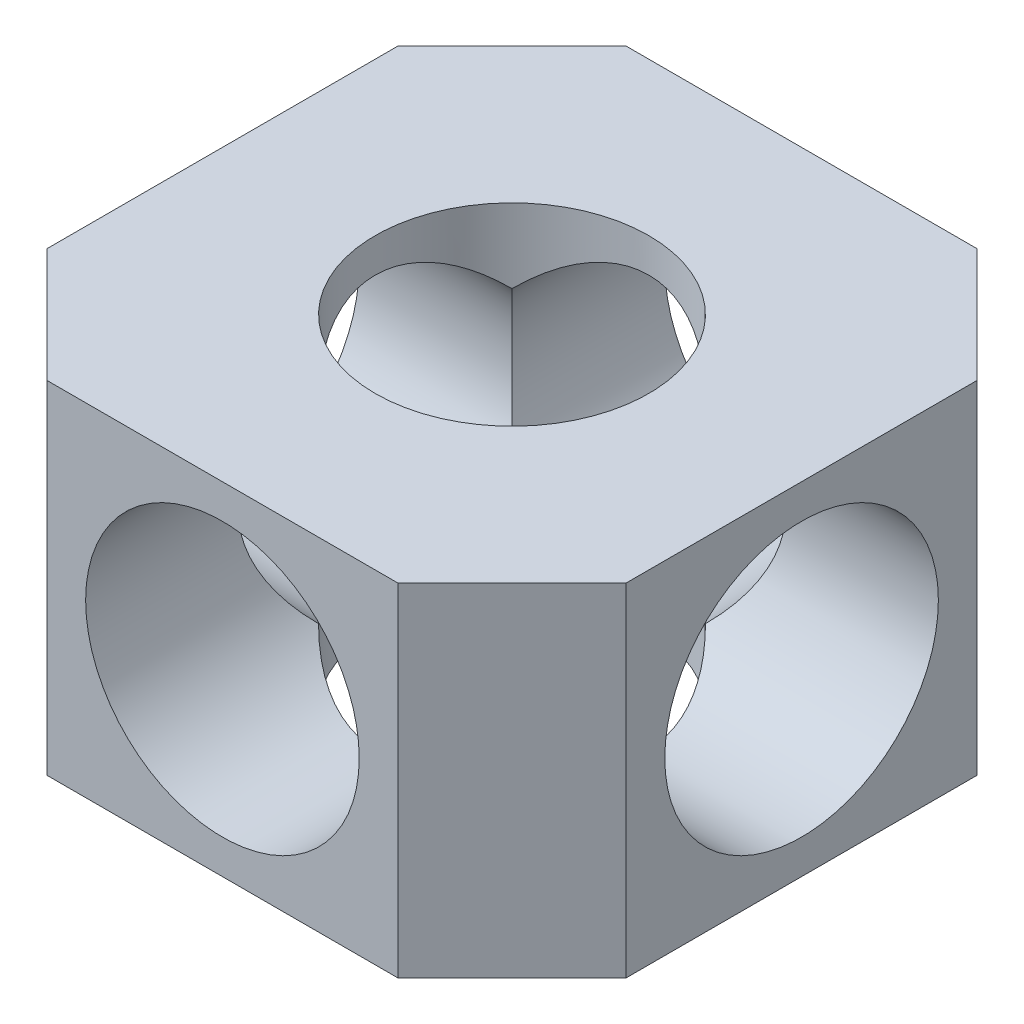
SolidWorks part; units mm, degrees
ref_plane "Front Plane" through (0, 0, 0) normal (0, 0, 1) x (1, 0, 0)
ref_plane "Top Plane" through (0, 0, 0) normal (0, 1, 0) x (1, 0, 0)
ref_plane "Right Plane" through (0, 0, 0) normal (1, 0, 0) x (0, 0, -1)
sketch "Sketch2" plane through (0, 0, 0) normal (0, 1, 0) x (1, 0, 0)
  line L0 (0, 0) -> (11024.3031, 0) construction
  line L2 (-12.7, 12.7) -> (12.7, 12.7)
  line L3 (-12.7, 12.7) -> (-12.7, -12.7)
  line L4 (-12.7, -12.7) -> (12.7, -12.7)
  line L5 (12.7, 12.7) -> (12.7, -12.7)
  line L6 (-12.7, 12.7) -> (12.7, -12.7) construction
  line L7 (-12.7, -12.7) -> (12.7, 12.7) construction
  point P3 (0, 0)
  dimension "D1" = 25.4
extrude "Boss-Extrude1" add sketch "Sketch2" along normal mid plane 15
chamfer "Chamfer1" distance 5 4 edges at (-12.7, 0, 12.7) (12.7, 0, 12.7) (-12.7, 0, -12.7) (12.7, 0, -12.7)
sketch "Sketch3" plane through (0, 7.5, 0) normal (0, 1, 0) x (1, 0, 0)
  circle A0 centre (0, 0) radius 6
  dimension "D1" = 12
extrude "Cut-Extrude1" cut sketch "Sketch3" against normal through all
sketch "Sketch4" plane through (0, 0, 12.7) normal (0, 0, 1) x (1, 0, 0)
  circle A0 centre (0, 0) radius 6
  dimension "D1" = 12
extrude "Cut-Extrude2" cut sketch "Sketch4" against normal up to next
pattern_circular "CirPattern1" count 4 over 360 about axis through (0, 7.5, 0) along (0, 1, 0) of "Cut-Extrude2"
